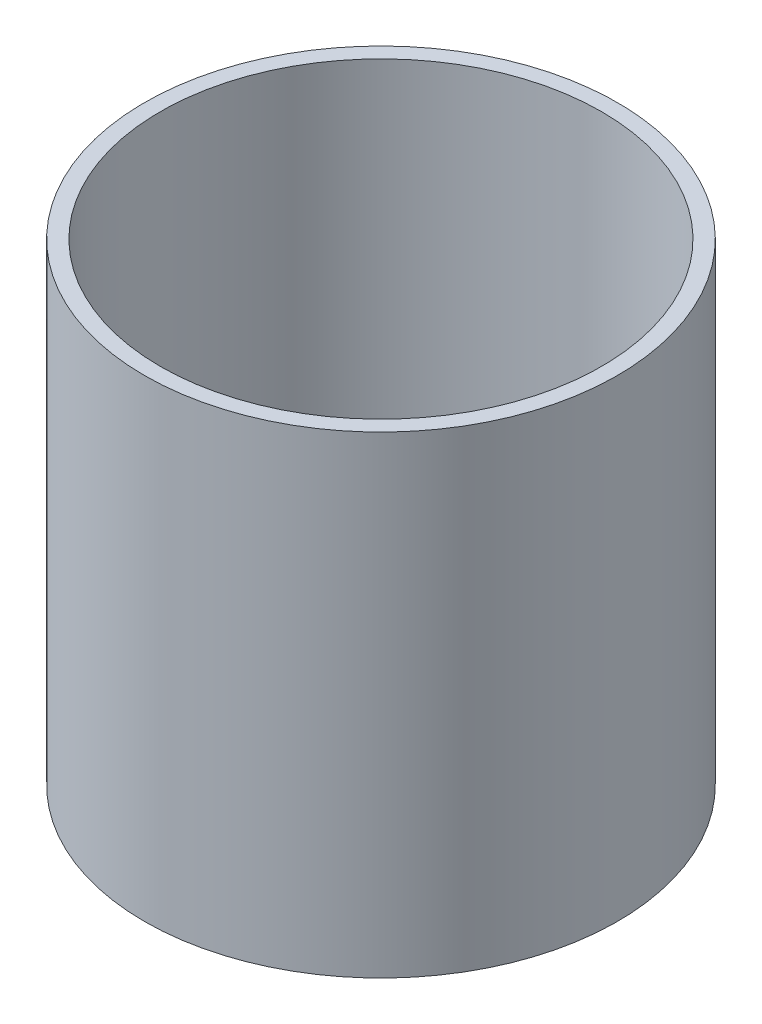
SolidWorks part; units mm, degrees
ref_plane "Front Plane" through (0, 0, 0) normal (0, 0, 1) x (1, 0, 0)
ref_plane "Top Plane" through (0, 0, 0) normal (0, 1, 0) x (1, 0, 0)
ref_plane "Right Plane" through (0, 0, 0) normal (1, 0, 0) x (0, 0, -1)
sketch "Sketch1" plane through (0, 0, 0) normal (0, 1, 0) x (1, 0, 0)
  circle A0 centre (0, 0) radius 75
  dimension "D1" = 150
extrude "Boss-Extrude1" add sketch "Sketch1" along normal mid plane 150
sketch "Sketch2" plane through (0, 0, 0) normal (0, 1, 0) x (1, 0, 0)
  circle A0 centre (0, 0) radius 70
  dimension "D1" = 140
extrude "Cut-Extrude1" cut sketch "Sketch2" against normal blind 95 and the other way through all
sketch "Sketch3" plane through (0, -95, 0) normal (0, 1, 0) x (1, 0, 0)
  circle A0 centre (0, 0) radius 7.5
  dimension "D1" = 15
extrude "Cut-Extrude2" cut sketch "Sketch3" against normal through all
